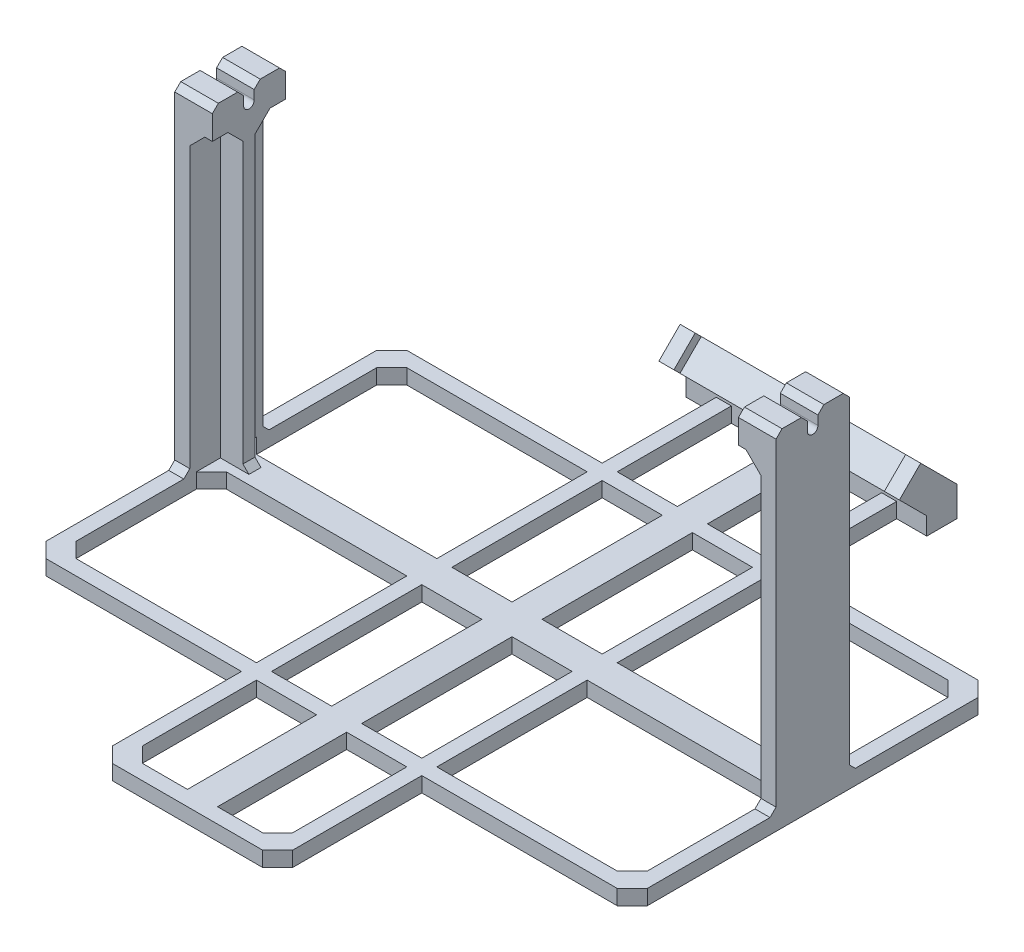
SolidWorks part; units mm, degrees
ref_plane "Front Plane" through (0, 0, 0) normal (0, 0, 1) x (1, 0, 0)
ref_plane "Top Plane" through (0, 0, 0) normal (0, 1, 0) x (1, 0, 0)
ref_plane "Right Plane" through (0, 0, 0) normal (1, 0, 0) x (0, 0, -1)
sketch "Sketch1" plane through (0, 0, 0) normal (0, 1, 0) x (1, 0, 0)
  line L0 (95, -55) -> (95, 55)
  line L1 (-100, -60) -> (100, -60)
  line L2 (-100, -60) -> (-100, 60)
  line L3 (-100, 60) -> (100, 60)
  line L4 (100, -60) -> (100, 60)
  line L5 (-100, -60) -> (100, 60) construction
  line L6 (-100, 60) -> (100, -60) construction
  line L7 (-95, 55) -> (95, 55)
  line L8 (-95, -55) -> (-95, 55)
  line L9 (-95, -55) -> (95, -55)
  point P0 (0, 0)
  dimension "D1" = 200
  dimension "D2" = 120
  dimension "D3" = 5
extrude "Boss-Extrude1" add sketch "Sketch1" along normal blind 5
sketch "Sketch2" plane through (0, 5, 0) normal (0, 1, 0) x (1, 0, 0)
  line L0 (-100, 60) -> (-100, -60) construction
  line L1 (100, -12.1758) -> (-100, -12.1758)
  line L2 (100, -12.1758) -> (100, 12.1758)
  line L3 (100, 12.1758) -> (-100, 12.1758)
  line L4 (-100, -12.1758) -> (-100, 12.1758)
  line L5 (100, -12.1758) -> (-100, 12.1758) construction
  line L6 (100, 12.1758) -> (-100, -12.1758) construction
  line L7 (-95, 55) -> (-95, -55) construction
  line L8 (95, -12.1758) -> (-95, -12.1758)
  line L9 (95, -12.1758) -> (95, 12.1758)
  line L10 (95, 12.1758) -> (-95, 12.1758)
  line L11 (-95, -12.1758) -> (-95, 12.1758)
  line L12 (95, -12.1758) -> (-95, 12.1758) construction
  line L13 (95, 12.1758) -> (-95, -12.1758) construction
  point P0 (0, 0)
  point P8 (0, 0)
  line M1 (100, -60) -> (100, 60)
  line M3 (-100, 60) -> (-100, -60)
  line M6 (-95, -55) -> (-95, 55)
  line M8 (95, 55) -> (95, -55)
extrude "Boss-Extrude2" add sketch "Sketch2" along normal blind 100 contours L3 L1 M6 M3 | L3 L1 M1 M8
sketch "Sketch3" plane through (0, 0, 0) normal (0, -1, 0) x (1, 0, 0)
  line L0 (95, 55) -> (95, -55) construction
  line L1 (-95, 5) -> (95, 5)
  line L2 (-95, 5) -> (-95, -5)
  line L3 (-95, -5) -> (95, -5)
  line L4 (95, 5) -> (95, -5)
  line L5 (-95, 5) -> (95, -5) construction
  line L6 (-95, -5) -> (95, 5) construction
  point P0 (0, 0)
  dimension "D1" = 10
extrude "Boss-Extrude3" add sketch "Sketch3" against normal up to surface (5 mm away) up to face at (0.3125, 5, 29.1724)
sketch "Sketch4" plane through (0, 105, 0) normal (0, 1, 0) x (1, 0, 0)
  line L0 (100, -12.1758) -> (95, -12.1758) construction
  line L1 (100, 12.1758) -> (87.5, 12.1758)
  line L2 (100, 12.1758) -> (100, -12.1758)
  line L3 (100, -12.1758) -> (87.5, -12.1758)
  line L4 (87.5, 12.1758) -> (87.5, -12.1758)
  line L5 (0, 0) -> (0, -27.2974) construction
  line L6 (-87.5, 12.1758) -> (-87.5, -12.1758)
  line L7 (-100, -12.1758) -> (-87.5, -12.1758)
  line L8 (-100, 12.1758) -> (-100, -12.1758)
  line L9 (-100, 12.1758) -> (-87.5, 12.1758)
  dimension "D1" = 12.5
extrude "Boss-Extrude4" add sketch "Sketch4" along normal blind 10
sketch "Sketch5" plane through (0, 0, 0) normal (0, 0, 1) x (1, 0, 0)
  line L0 (0, 0) -> (0, 35.6266) construction
  line L1 (-87.5, 105) -> (-95, 105)
  line L2 (-87.5, 105) -> (-87.5, 5)
  line L3 (-87.5, 5) -> (-95, 5)
  line L4 (-95, 105) -> (-95, 5)
  line L5 (-100, 0) -> (100, 0) construction
  line L6 (95, 105) -> (95, 5)
  line L7 (87.5, 5) -> (95, 5)
  line L8 (87.5, 105) -> (87.5, 5)
  line L9 (87.5, 105) -> (95, 105)
extrude "Boss-Extrude5" add sketch "Sketch5" along normal blind 2 and the other way blind 2
sketch "Sketch6" plane through (100, 0, 0) normal (1, 0, 0) x (0, 0, -1)
  line L0 (0, 120) -> (0, 110) construction
  line L1 (-12.1758, 115) -> (12.1758, 115) construction
  line L2 (1.75, 120) -> (1.75, 110)
  line L3 (-1.75, 120) -> (-1.75, 110)
  arc A0 (1.75, 120) -> (-1.75, 120) centre (0, 120) ccw
  arc A1 (-1.75, 110) -> (1.75, 110) centre (0, 110) ccw
  point P5 (0, 115)
  dimension "D1" = 3.5
  dimension "D2" = 10
extrude "Cut-Extrude1" cut sketch "Sketch6" against normal through all
sketch "Sketch7" plane through (0, 5, 0) normal (0, 1, 0) x (1, 0, 0)
  line L0 (25, -102.95) -> (25, 102.95)
  line L1 (30, -107.95) -> (-30, -107.95)
  line L2 (30, -107.95) -> (30, 107.95)
  line L3 (30, 107.95) -> (-30, 107.95)
  line L4 (-30, -107.95) -> (-30, 107.95)
  line L5 (30, -107.95) -> (-30, 107.95) construction
  line L6 (30, 107.95) -> (-30, -107.95) construction
  line L7 (25, 102.95) -> (-25, 102.95)
  line L8 (-25, -102.95) -> (-25, 102.95)
  line L9 (25, -102.95) -> (-25, -102.95)
  point P0 (0, 0)
  dimension "D1" = 60
  dimension "D2" = 215.9
  dimension "D3" = 5
extrude "Boss-Extrude6" add sketch "Sketch7" against normal up to surface (5 mm away) up to face at (0, 0, 30)
chamfer "Chamfer1" distance 2 angle 45 14 edges at (-93.75, 115, -1.75) (-93.75, 115, 1.75) (93.75, 115, 1.75) (93.75, 115, -1.75) (97.5, 5, 12.1758) (87.5, 5, 0) (97.5, 5, -12.1758) (-87.5, 5, 0) (-93.75, 115, 12.1758) (-93.75, 115, -12.1758) (93.75, 115, -12.1758) (93.75, 115, 12.1758)
sketch "Sketch8" plane through (0, 5, 0) normal (0, 1, 0) x (1, 0, 0)
  line L0 (25, 102.95) -> (-25, 102.95) construction
  line L1 (5, -102.95) -> (-5, -102.95)
  line L2 (5, -102.95) -> (5, 102.95)
  line L3 (5, 102.95) -> (-5, 102.95)
  line L4 (-5, -102.95) -> (-5, 102.95)
  line L5 (5, -102.95) -> (-5, 102.95) construction
  line L6 (5, 102.95) -> (-5, -102.95) construction
  point P0 (0, 0)
  dimension "D1" = 10
extrude "Boss-Extrude7" add sketch "Sketch8" against normal up to surface (5 mm away) up to face at (-62.5, 0, 30)
chamfer "Chamfer2" distance 5 angle 45 36 edges at (-91.25, 105, -2) (-91.25, 105, 2) (91.25, 105, -2) (91.25, 105, 2) (-95, 2.5, 55) (95, 2.5, 55) (95, 2.5, -55) (-95, 2.5, -55) (-30, 2.5, 107.95) (30, 2.5, -107.95) (-25, 2.5, -102.95) (25, 2.5, 102.95) (-30, 2.5, -107.95) (30, 2.5, 107.95) (-25, 2.5, 102.95) (25, 2.5, -102.95) (95, 2.5, 5) (95, 2.5, -5) (-95, 2.5, -5) (-95, 2.5, 5) (100, 2.5, 60) (-100, 2.5, 60) (-100, 2.5, -60) (100, 2.5, -60)
sketch "Sketch9" plane through (0, 0, 0) normal (1, 0, 0) x (0, 0, -1)
  line L0 (107.95, 5) -> (107.95, 10)
  line L1 (107.95, 10) -> (97.95, 20)
  line L2 (97.95, 20) -> (97.95, 5)
  line L3 (60, 5) -> (102.95, 5) construction
  line L4 (97.95, 5) -> (107.95, 5)
  line L5 (107.95, 5) -> (107.95, 0)
  line L6 (107.95, 0) -> (97.95, 0)
  line L7 (97.95, 0) -> (97.95, 5)
  dimension "D1" = 5
  dimension "D2" = 45
  dimension "D3" = 10
extrude "Boss-Extrude8" add sketch "Sketch9" along normal blind 40 and the other way blind 40
sketch "Sketch10" plane through (0, 58.975, -58.975) normal (0, 0.7071, -0.7071) x (1, 0, 0)
  line L0 (0, 0) -> (0, 84.546) construction
  line L1 (40, 69.2611) -> (35, 69.2611)
  line L2 (40, 69.2611) -> (40, 52.2611)
  line L3 (40, 52.2611) -> (35, 52.2611)
  line L4 (35, 69.2611) -> (35, 52.2611)
  line L5 (-35, 69.2611) -> (-35, 52.2611)
  line L6 (-40, 52.2611) -> (-35, 52.2611)
  line L7 (-40, 69.2611) -> (-40, 52.2611)
  line L8 (-40, 69.2611) -> (-35, 69.2611)
  line L9 (-40, 55.119) -> (40, 55.119) construction
  line L10 (35, 69.2611) -> (-35, 69.2611)
  line L11 (35, 69.2611) -> (35, 55.119)
  line L12 (35, 55.119) -> (-35, 55.119)
  line L13 (-35, 69.2611) -> (-35, 55.119)
  circle A0 centre (37.425, 56.3102) radius 1.27
  circle A1 centre (-37.425, 56.3102) radius 1.27
  line M1 (-40, 55.119) -> (40, 55.119)
  line M2 (40, 55.119) -> (40, 69.2611)
  line M3 (40, 69.2611) -> (-40, 69.2611)
  line M4 (-40, 69.2611) -> (-40, 55.119)
  dimension "D3" = 2.54
  dimension "D1" = 17
  dimension "D2" = 5
extrude "Boss-Extrude9" add sketch "Sketch10" against normal blind 10 contours L4 A0 M3 M1 M2 | L4 L3 L2 M1 | L0 L12 L4 M3 | L0 L10 L5 M1 | L7 L6 L5 M1 | L5 A1 M3 M4 M1
sketch "Sketch12" plane through (0, 51.9039, -51.9039) normal (0, -0.7071, 0.7071) x (1, 0, 0)
  circle A2 centre (37.425, -56.3102) radius 1.27
  circle A3 centre (37.425, -56.3102) radius 1.27
  circle A5 centre (-37.425, -56.3102) radius 1.27
  circle A6 centre (-37.425, -56.3102) radius 1.27
  dimension "D1" = 0
  dimension "D2" = 0
extrude "Cut-Extrude2" cut sketch "Sketch12" against normal through all
